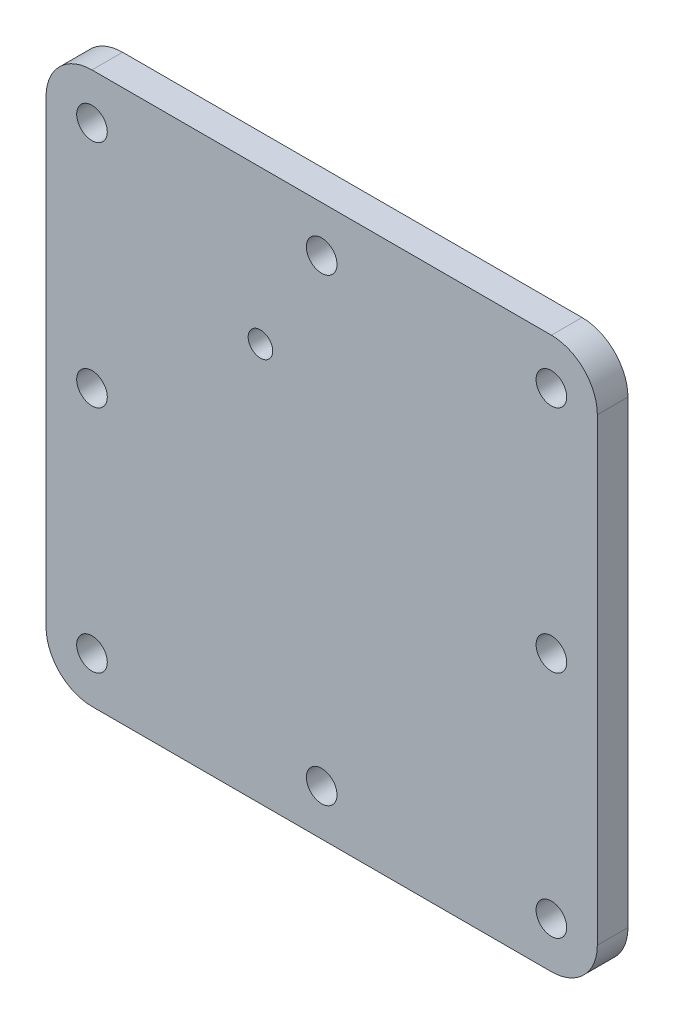
SolidWorks part; units mm, degrees
ref_plane "Front Plane" through (0, 0, 0) normal (0, 0, 1) x (1, 0, 0)
ref_plane "Top Plane" through (0, 0, 0) normal (0, 1, 0) x (1, 0, 0)
ref_plane "Right Plane" through (0, 0, 0) normal (1, 0, 0) x (0, 0, -1)
sketch "Sketch2" plane through (0, 0, 0) normal (0, 0, 1) x (1, 0, 0)
  line L0 (-75, 75) -> (75, 75) construction
  line L1 (-75, 90) -> (75, 90)
  line L2 (-90, 75) -> (-90, -75)
  line L3 (-75, -90) -> (75, -90)
  line L4 (90, 75) -> (90, -75)
  line L5 (-90, 90) -> (90, -90) construction
  line L6 (-90, -90) -> (90, 90) construction
  line L7 (75, 75) -> (75, -75) construction
  line L8 (75, -75) -> (-75, -75) construction
  line L9 (-75, -75) -> (-75, 75) construction
  line L15 (-60, 60) -> (60, -60) construction
  line L16 (-60, -60) -> (60, 60) construction
  arc A0 (-90, -75) -> (-75, -90) centre (-75, -75) ccw
  arc A1 (75, -90) -> (90, -75) centre (75, -75) ccw
  arc A2 (75, 90) -> (90, 75) centre (75, 75) cw
  arc A3 (-75, 90) -> (-90, 75) centre (-75, 75) ccw
  circle A4 centre (-75, 75) radius 5
  circle A5 centre (0, 75) radius 5
  circle A6 centre (75, 75) radius 5
  circle A7 centre (-75, 0) radius 5
  circle A8 centre (0, 0) radius 5 construction
  circle A9 centre (75, 0) radius 5
  circle A10 centre (-75, -75) radius 5
  circle A11 centre (0, -75) radius 5
  circle A12 centre (75, -75) radius 5
  point P0 (0, 0)
  dimension "D3" = 15
  dimension "D4" = 10
  dimension "D1" = 180
  dimension "D2" = 180
  dimension "D8" = 120
  dimension "D7" = 3
extrude "Boss-Extrude1" add sketch "Sketch2" along normal blind 10
sketch "Sketch3" plane through (0, 0, 10) normal (0, 0, 1) x (1, 0, 0)
  line L1 (-50, 50) -> (50, 50) construction
  line L2 (-50, 50) -> (-50, -50) construction
  line L3 (-50, -50) -> (50, -50) construction
  line L4 (50, 50) -> (50, -50) construction
  line L5 (-50, 50) -> (50, -50) construction
  line L6 (-50, -50) -> (50, 50) construction
  line L7 (0, 0) -> (-40, 0) construction
  line L8 (0, 0) -> (0, 40) construction
  line L9 (0, 40) -> (-40, 40) construction
  line L10 (-40, 0) -> (-40, 40) construction
  circle A0 centre (0, 0) radius 4 construction
  point P0 (0, 0)
  dimension "D5" = 8
  dimension "D1" = 100
  dimension "D2" = 100
  dimension "D3" = 40
  dimension "D4" = 40
sketch "Sketch5" plane through (0, 0, 10) normal (0, 0, 1) x (1, 0, 0)
  line L0 (0, 40) -> (-40, 40) construction
  circle A0 centre (-20, 40) radius 4
  dimension "D1" = 8
extrude "Cut-Extrude4" cut sketch "Sketch5" against normal blind 10
